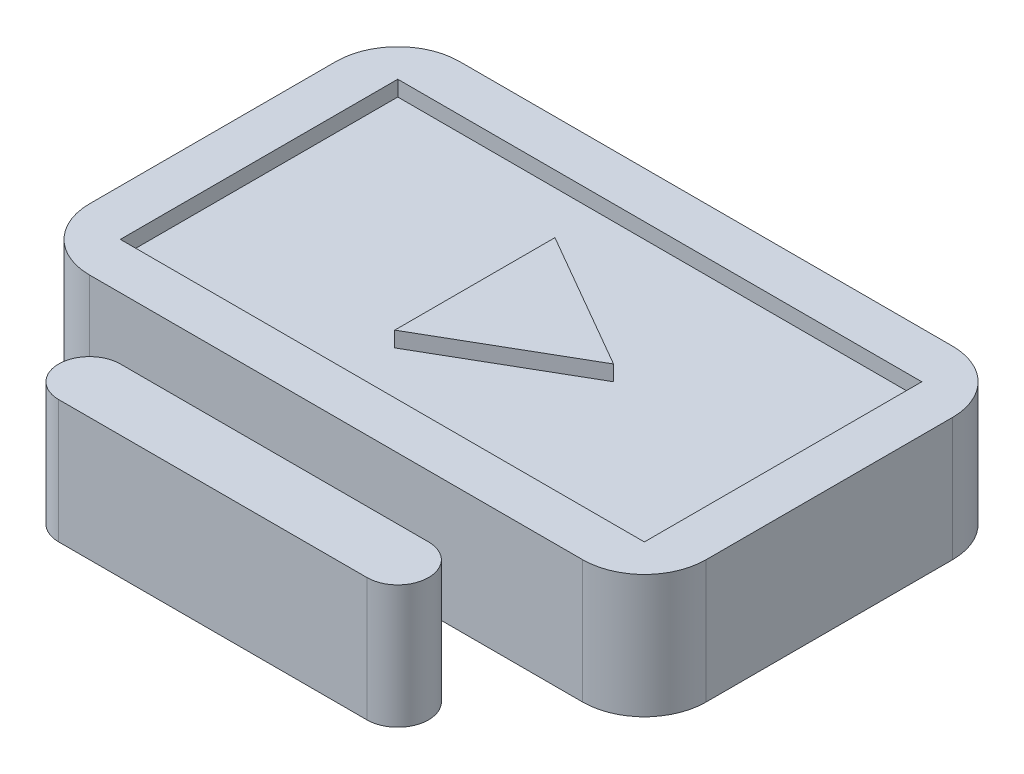
SolidWorks part; units mm, degrees
material "6061-T4 (SS)"
ref_plane "Front" through (0, 0, 0) normal (0, 0, 1) x (1, 0, 0)
ref_plane "Top" through (0, 0, 0) normal (0, 1, 0) x (1, 0, 0)
ref_plane "Right" through (0, 0, 0) normal (1, 0, 0) x (0, 0, -1)
sketch "Sketch2" plane through (0, 0, 0) normal (0, 1, 0) x (1, 0, 0)
  line L0 (-63.5, 0) -> (63.5, 0) construction
  line L1 (-63.5, 12.7) -> (63.5, 12.7)
  line L2 (-63.5, -12.7) -> (63.5, -12.7)
  line L3 (0, 0) -> (0, 38.1) construction
  line L4 (12.7, 0) -> (12.7, 38.1)
  line L5 (-12.7, 0) -> (-12.7, 38.1)
  line L6 (-12.7, 0) -> (-12.7, 38.1) construction
  line L7 (-127, 190.5) -> (127, 190.5)
  line L8 (-127, 190.5) -> (-127, 38.1)
  line L9 (-127, 38.1) -> (127, 38.1)
  line L10 (127, 190.5) -> (127, 38.1)
  line L11 (-127, 190.5) -> (127, 38.1) construction
  line L12 (-127, 38.1) -> (127, 190.5) construction
  arc A0 (-63.5, 12.7) -> (-63.5, -12.7) centre (-63.5, 0) ccw
  arc A1 (63.5, -12.7) -> (63.5, 12.7) centre (63.5, 0) ccw
  point P2 (0, 0)
  point P14 (0, 114.3)
  point P19 (-12.7, 85.5656)
  point P22 (-12.7, 82.9089)
  point P23 (129.772, 79.7824)
  point P24 (0, 0)
  point P25 (98.8687, 68.9392)
  point P26 (107.0011, 189.8415)
  point P27 (0, 116.6495)
  dimension "D1" = 25.4
  dimension "D2" = 127
  dimension "D5" = 254
  dimension "D6" = 152.4
  dimension "D7" = 25.4
  dimension "D3" = 12.7
  dimension "D4" = 12.7
extrude "Boss-Extrude1" add sketch "Sketch2" along normal blind 50.8
fillet "Fillet1" radius 25.4 4 edges at (127, 25.4, -38.1) (-127, 25.4, -38.1) (-127, 25.4, -190.5) (127, 25.4, -190.5)
sketch "Sketch4" plane through (0, 50.8, 0) normal (0, 1, 0) x (1, 0, 0)
  line L0 (-127, 114.3) -> (127, 114.3) construction
  line L1 (-127, 165.1) -> (-127, 63.5) construction
  line L2 (127, 165.1) -> (127, 63.5) construction
  line L3 (-101.6, 190.5) -> (101.6, 190.5) construction
  line L4 (-107.95, 57.15) -> (107.95, 57.15)
  line L5 (-107.95, 57.15) -> (-107.95, 171.45)
  line L6 (-107.95, 171.45) -> (107.95, 171.45)
  line L7 (107.95, 57.15) -> (107.95, 171.45)
  line L8 (-107.95, 57.15) -> (107.95, 171.45) construction
  line L9 (-107.95, 171.45) -> (107.95, 57.15) construction
  point P6 (0, 114.3)
  dimension "D1" = 19.05
  dimension "D2" = 19.05
extrude "Cut-Extrude1" cut sketch "Sketch4" against normal blind 6.35
sketch "Sketch5" plane through (0, 44.45, 0) normal (0, 1, 0) x (1, 0, 0)
  line L0 (0, 171.45) -> (0, 57.15) construction
  line L1 (107.95, 171.45) -> (-107.95, 171.45) construction
  line L2 (-107.95, 57.15) -> (107.95, 57.15) construction
  line L4 (38.1, 114.3) -> (-19.05, 147.2956)
  line L5 (-19.05, 147.2956) -> (-19.05, 81.3044)
  line L6 (-19.05, 81.3044) -> (38.1, 114.3)
  circle A0 centre (0, 114.3) radius 19.05 construction
  dimension "D1" = 38.1
extrude "Boss-Extrude2" add sketch "Sketch5" along normal up to surface (6.35 mm away) up to face at (0, 50.8, -114.3)
sketch "Sketch6" plane through (0, 50.8, 0) normal (0, 1, 0) x (1, 0, 0)
  line L1 (-12.7, 38.1) -> (12.7, 38.1)
  line L2 (-12.7, 38.1) -> (-12.7, 12.7)
  line L3 (-12.7, 12.7) -> (12.7, 12.7)
  line L4 (12.7, 38.1) -> (12.7, 12.7)
extrude "Cut-Extrude2" cut sketch "Sketch6" against normal blind 25.4
equation "\"D2@Sketch4\"=\"D1@Sketch4\""
